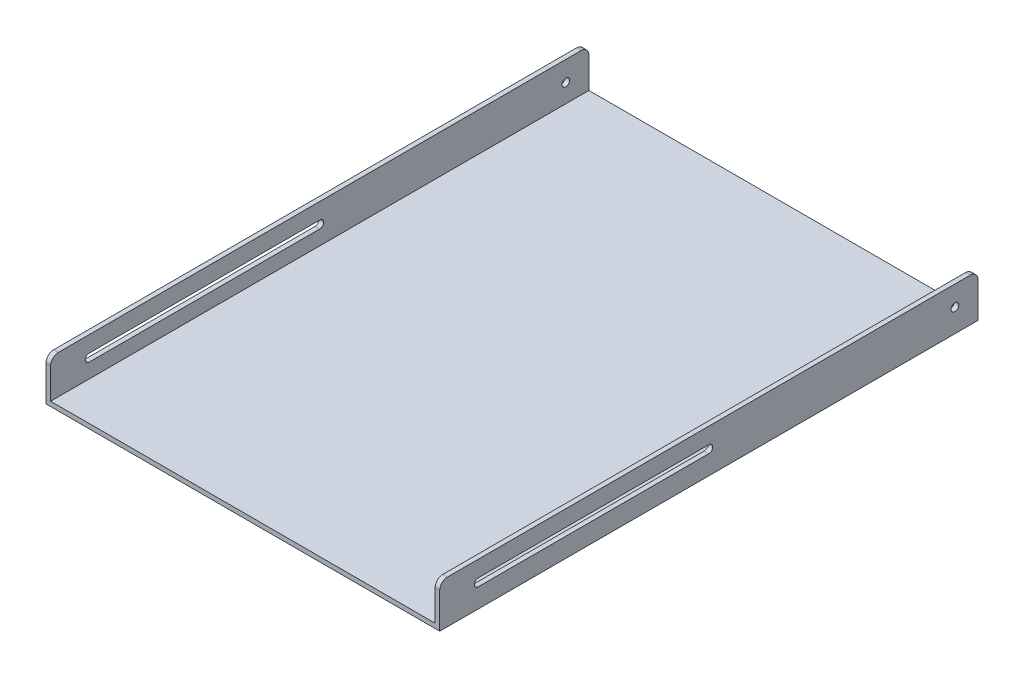
SolidWorks part; units mm, degrees
ref_plane "Front Plane" through (0, 0, 0) normal (0, 0, 1) x (1, 0, 0)
ref_plane "Top Plane" through (0, 0, 0) normal (0, 1, 0) x (1, 0, 0)
ref_plane "Right Plane" through (0, 0, 0) normal (1, 0, 0) x (0, 0, -1)
sketch "Sketch2" plane through (0, 0, 0) normal (0, 0, 1) x (1, 0, 0)
  line L0 (-250, 50) -> (-250, 0)
  line L1 (-250, 0) -> (250, 0)
  line L2 (250, 0) -> (250, 50)
  point P2 (-250, 25)
  dimension "D1" = 500
  dimension "D2" = 250
  dimension "D3" = 50
  dimension "D4" = 50
extrude "Extrude-Thin1" add sketch "Sketch2" along normal mid plane 700 thin
sketch "Sketch3" plane through (256, 0, 0) normal (1, 0, 0) x (0, 0, -1)
  line L0 (0, 24) -> (-300, 24) construction
  line L1 (0, 19) -> (-300, 19)
  line L2 (0, 29) -> (-300, 29)
  line L3 (350, -6) -> (350, 50) construction
  line L4 (-350, -6) -> (350, -6) construction
  circle A0 centre (320, 24) radius 5
  arc A1 (0, 19) -> (0, 29) centre (0, 24) ccw
  arc A2 (-300, 29) -> (-300, 19) centre (-300, 24) ccw
  point P4 (-150, 24)
  dimension "D1" = 10
  dimension "D2" = 30
  dimension "D3" = 30
  dimension "D4" = 150
  dimension "D5" = 300
  dimension "D6" = 10
extrude "Cut-Extrude1" cut sketch "Sketch3" against normal through all
fillet "Fillet1" radius 10 4 edges at (-253, 50, -350) (253, 50, -350) (253, 50, 350) (-253, 50, 350)
